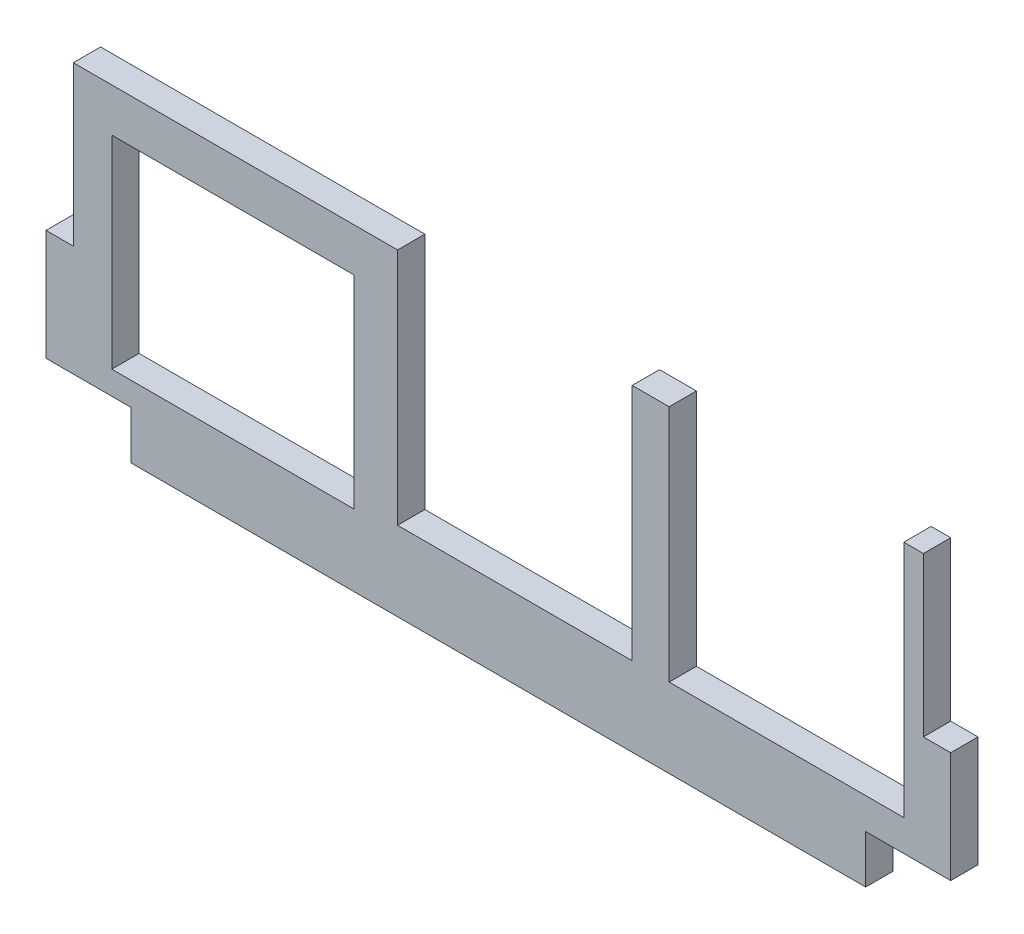
SolidWorks part; units mm, degrees
ref_plane "Front Plane" through (0, 0, 0) normal (0, 0, 1) x (1, 0, 0)
ref_plane "Top Plane" through (0, 0, 0) normal (0, 1, 0) x (1, 0, 0)
ref_plane "Right Plane" through (0, 0, 0) normal (1, 0, 0) x (0, 0, -1)
sketch "Sketch1" plane through (0, 0, 0) normal (0, 0, 1) x (1, 0, 0)
  line L0 (-1.8034, 12.0396) -> (0, 12.0396) construction
  line L1 (-1.8034, 12.0396) -> (-1.8034, 4.7244) construction
  line L2 (3.81, 1.5494) -> (3.81, 4.7244) construction
  line L3 (3.81, 1.5494) -> (52.324, 1.5494) construction
  line L4 (52.324, 1.5494) -> (52.324, 4.7244) construction
  line L5 (57.9374, 12.0396) -> (56.134, 12.0396) construction
  line L6 (57.9374, 4.7244) -> (57.9374, 12.0396) construction
  line L7 (-1.8034, 12.0396) -> (0, 12.0396)
  line L8 (-1.8034, 12.0396) -> (-1.8034, 4.7244)
  line L9 (3.81, 1.5494) -> (3.81, 4.7244)
  line L10 (3.81, 1.5494) -> (52.324, 1.5494)
  line L11 (52.324, 1.5494) -> (52.324, 4.7244)
  line L12 (57.9374, 12.0396) -> (56.134, 12.0396)
  line L13 (57.9374, 4.7244) -> (57.9374, 12.0396)
  line L14 (-1.8034, 4.7244) -> (3.81, 4.7244)
  line L15 (52.324, 4.7244) -> (57.9374, 4.7244)
  line L16 (0, 12.0396) -> (0, 19.6596)
  line L17 (0, 24.0792) -> (0, 4.7244) construction
  line L18 (0, 19.6596) -> (2.54, 19.6596)
  line L19 (2.54, 19.6596) -> (2.54, 6.2738)
  line L20 (2.54, 6.2738) -> (18.542, 6.2738)
  line L21 (18.542, 6.2738) -> (18.542, 22.5298)
  line L22 (18.542, 22.5298) -> (21.4122, 22.5298)
  line L23 (21.4122, 22.5298) -> (21.4122, 6.7818)
  line L24 (21.4122, 6.7818) -> (36.9062, 6.7818)
  line L25 (36.9062, 6.7818) -> (36.9062, 22.5298)
  line L26 (36.9062, 22.5298) -> (39.3446, 22.5298)
  line L27 (39.3446, 22.5298) -> (39.3446, 6.7818)
  line L28 (39.3446, 6.7818) -> (54.8386, 6.7818)
  line L29 (54.8386, 6.7818) -> (54.8386, 22.5298)
  line L30 (54.8386, 22.5298) -> (56.134, 22.5298)
  line L31 (56.134, 24.0792) -> (56.134, 4.7244) construction
  line L32 (56.134, 22.5298) -> (56.134, 12.0396)
  line L33 (23.876, 4.7244) -> (0, 4.7244) construction
  point P25 (11.938, 4.7244)
  dimension "D1" = 14.9352
  dimension "D2" = 2.54
  dimension "D3" = 2.8702
  dimension "D4" = 2.4384
  dimension "D5" = 15.494
  dimension "D6" = 16.002
  dimension "D7" = 1.5494
  dimension "D8" = 15.748
  dimension "D9" = 2.0574
extrude "Boss-Extrude1" add sketch "Sketch1" along normal blind 1.8034
sketch "Sketch2" plane through (0, 0, 1.8034) normal (0, 0, 1) x (1, 0, 0)
  line L1 (0, 19.6596) -> (18.542, 19.6596)
  line L2 (0, 19.6596) -> (0, 22.5298)
  line L3 (0, 22.5298) -> (18.542, 22.5298)
  line L4 (18.542, 19.6596) -> (18.542, 22.5298)
extrude "Boss-Extrude2" add sketch "Sketch2" against normal up to vertex (1.8034 mm away) up to point (18.542, 22.5298, 0)
